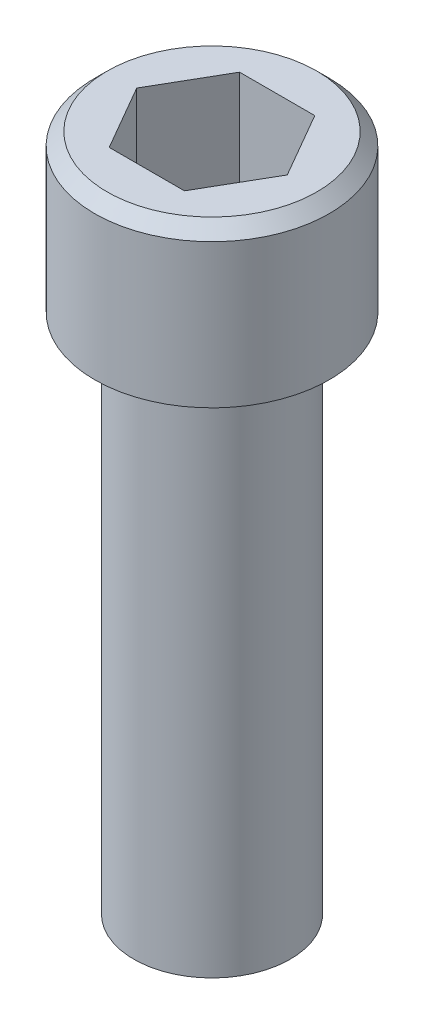
SolidWorks part; units mm, degrees
ref_plane "Plane1" through (0, 0, 0) normal (0, 0, 1) x (1, 0, 0)
ref_plane "Plane2" through (0, 0, 0) normal (0, 1, 0) x (1, 0, 0)
ref_plane "Plane3" through (0, 0, 0) normal (1, 0, 0) x (0, 0, -1)
sketch "Sketch1" plane through (0, 0, 0) normal (0, 0, 1) x (1, 0, 0)
  line L0 (0, 0) -> (0, 43.6223) construction
  line L1 (4.7625, 0) -> (7.1437, 0)
  line L2 (7.1437, 0) -> (7.1437, 9.525)
  line L3 (7.1437, 9.525) -> (0, 9.525)
  line L4 (0, 9.525) -> (0, -31.75)
  line L5 (0, -31.75) -> (4.7625, -31.75)
  line L6 (4.7625, -31.75) -> (4.7625, 0)
  line L7 (50, 0) -> (-50, 0) construction
  dimension "D1" = 14.2875
  dimension "D2" = 9.525
  dimension "D3" = 9.525
  dimension "D4" = 31.75
revolve "Base-Revolve" add sketch "Sketch1" angle 360 about L0
sketch "Sketch2" plane through (0, 9.525, 0) normal (0, 1, 0) x (-1, 0, 0)
  line L0 (2.2914, -3.9688) -> (-2.2914, -3.9688)
  line L1 (-4.5827, 0) -> (-2.2914, -3.9688)
  line L2 (0, 0) -> (0, -3.9688) construction
  line L3 (0, 0) -> (-4.5827, 0) construction
  line L4 (4.5827, 0) -> (2.2914, -3.9688)
  line L5 (4.5827, 0) -> (2.2914, 3.9688)
  line L6 (-4.5827, 0) -> (-2.2914, 3.9688)
  line L7 (2.2914, 3.9688) -> (-2.2914, 3.9688)
  circle A0 centre (0, 0) radius 3.9688 construction
  point P12 (0, -3.9688)
  point P14 (0, 3.9688)
  dimension "D2" = 7.9375
extrude "Cut-Extrude1" cut sketch "Sketch2" against normal blind 6.35
chamfer "Chamfer1" distance 0.762 angle 45 1 edges at (0, 9.525, -7.1437)
chamfer "Chamfer2" [suppressed] distance 0.762 angle 45
